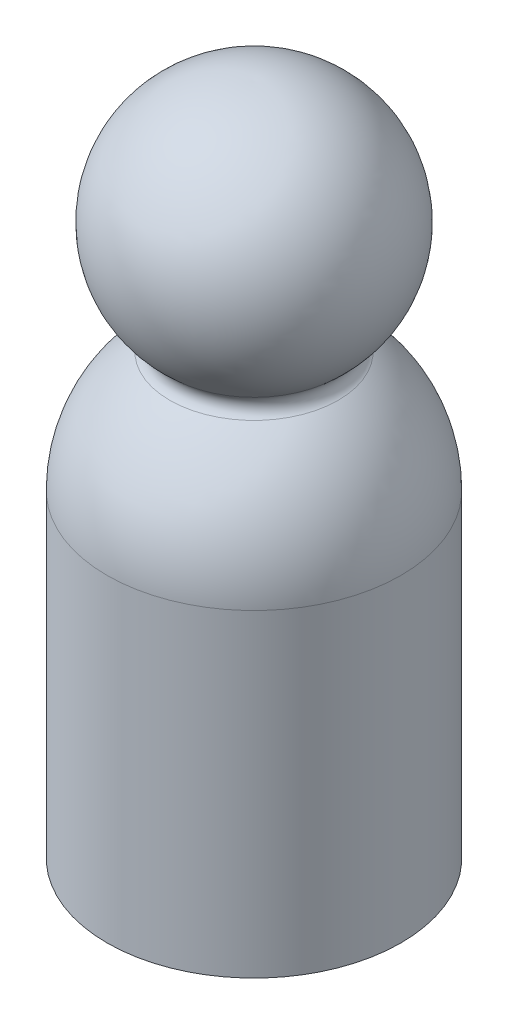
SolidWorks part; units mm, degrees
ref_plane "Front Plane" through (0, 0, 0) normal (0, 0, 1) x (1, 0, 0)
ref_plane "Top Plane" through (0, 0, 0) normal (0, 1, 0) x (1, 0, 0)
ref_plane "Right Plane" through (0, 0, 0) normal (1, 0, 0) x (0, 0, -1)
sketch "Sketch1" plane through (0, 0, 0) normal (0, 0, 1) x (1, 0, 0)
  line L0 (0, 0) -> (0, 69.2249) construction
  line L1 (12, 22.2446) -> (12, -3.7554)
  line L2 (0, 51.2402) -> (0, -3.7554)
  line L3 (0, -3.7554) -> (12, -3.7554)
  arc A0 (6.8054, 33.6529) -> (0, 51.2402) centre (0.2964, 41.2446) ccw
  arc A1 (6.8827, 32.0746) -> (12, 22.2446) centre (0, 22.2446) cw
  arc A2 (6.8054, 33.6529) -> (6.8827, 32.0746) centre (7.4563, 32.8937) ccw
  dimension "D1" = 20
  dimension "D5" = 12
  dimension "D6" = 1
  dimension "D2" = 26
  dimension "D3" = 12
  dimension "D4" = 19
revolve "Revolve1" add sketch "Sketch1" angle 360 about L0
